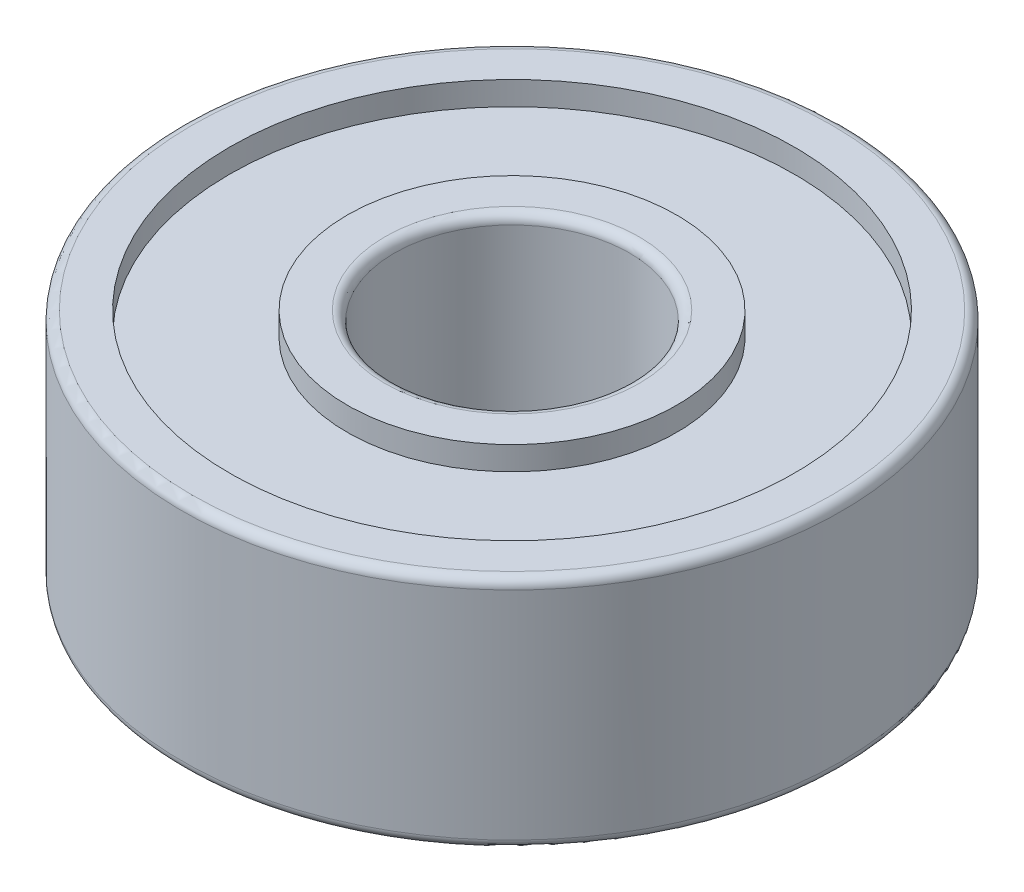
SolidWorks part; units mm, degrees
ref_plane "Front Plane" through (0, 0, 0) normal (0, 0, 1) x (1, 0, 0)
ref_plane "Top Plane" through (0, 0, 0) normal (0, 1, 0) x (1, 0, 0)
ref_plane "Right Plane" through (0, 0, 0) normal (1, 0, 0) x (0, 0, -1)
sketch "Sketch1" plane through (0, 0, 0) normal (0, 0, 1) x (1, 0, 0)
  line L0 (0, 5) -> (0, 0) construction
  line L1 (-2.5, 0) -> (-3.5, 0)
  line L2 (-3.5, 0) -> (-3.5, 0.5)
  line L3 (-3.5, 0.5) -> (-6, 0.5)
  line L4 (-6, 0.5) -> (-6, 0)
  line L5 (-6, 0) -> (-7, 0)
  line L6 (-7, 0) -> (-7, 5)
  line L7 (-7, 5) -> (-6, 5)
  line L8 (-6, 5) -> (-6, 4.5)
  line L9 (-6, 4.5) -> (-3.5, 4.5)
  line L10 (-3.5, 4.5) -> (-3.5, 5)
  line L11 (-3.5, 5) -> (-2.5, 5)
  line L12 (-2.5, 5) -> (-2.5, 0)
  dimension "D2_s" = 5
  dimension "D1._2" = 14
  dimension "MSM_8" = 7
  dimension "MSM_9" = 12
  dimension "B_2" = 5
  dimension "MSM_10" = 4
revolve "Revolve1" add sketch "Sketch1" angle 360 about L0
fillet "Fillet1" radius 0.2 4 edges at (-7, 0, 0) (-7, 5, 0) (-2.5, 0, 0) (-2.5, 5, 0)
